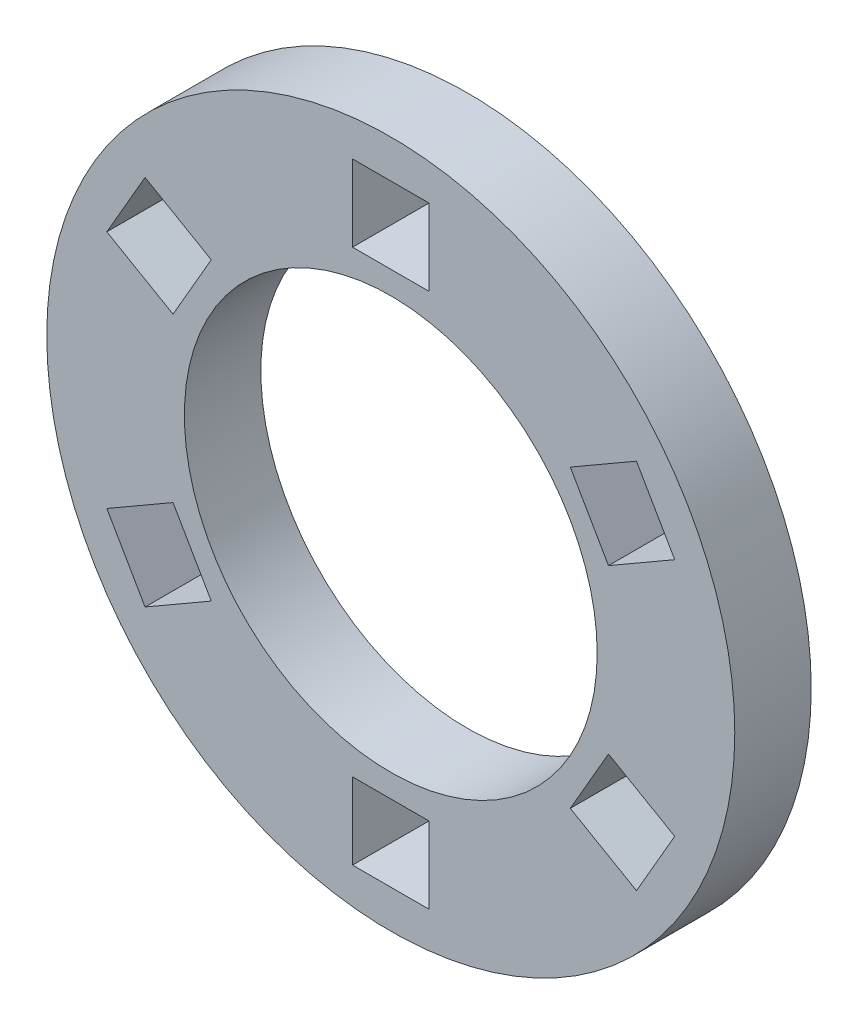
SolidWorks part; units mm, degrees
ref_plane "Front Plane" through (0, 0, 0) normal (0, 0, 1) x (1, 0, 0)
ref_plane "Top Plane" through (0, 0, 0) normal (0, 1, 0) x (1, 0, 0)
ref_plane "Right Plane" through (0, 0, 0) normal (1, 0, 0) x (0, 0, -1)
sketch "Sketch1" plane through (0, 0, 0) normal (0, 0, 1) x (1, 0, 0)
  line L0 (-22.5, 0) -> (22.5, 0) construction
  line L7 (-2.5, 20) -> (2.5, 20)
  line L8 (-2.5, 20) -> (-2.5, 15)
  line L9 (-2.5, 15) -> (2.5, 15)
  line L10 (2.5, 20) -> (2.5, 15)
  line L23 (0, 22.5) -> (0, -22.5) construction
  line L24 (18.5705, 7.8349) -> (14.2404, 5.3349)
  line L25 (11.7404, 9.6651) -> (14.2404, 5.3349)
  line L26 (16.0705, 12.1651) -> (11.7404, 9.6651)
  line L27 (16.0705, 12.1651) -> (18.5705, 7.8349)
  line L28 (16.0705, -12.1651) -> (11.7404, -9.6651)
  line L29 (14.2404, -5.3349) -> (11.7404, -9.6651)
  line L30 (18.5705, -7.8349) -> (14.2404, -5.3349)
  line L31 (18.5705, -7.8349) -> (16.0705, -12.1651)
  line L32 (-2.5, -20) -> (-2.5, -15)
  line L33 (2.5, -15) -> (-2.5, -15)
  line L34 (2.5, -20) -> (2.5, -15)
  line L35 (2.5, -20) -> (-2.5, -20)
  line L36 (-18.5705, -7.8349) -> (-14.2404, -5.3349)
  line L37 (-11.7404, -9.6651) -> (-14.2404, -5.3349)
  line L38 (-16.0705, -12.1651) -> (-11.7404, -9.6651)
  line L39 (-16.0705, -12.1651) -> (-18.5705, -7.8349)
  line L40 (-16.0705, 12.1651) -> (-11.7404, 9.6651)
  line L41 (-14.2404, 5.3349) -> (-11.7404, 9.6651)
  line L42 (-18.5705, 7.8349) -> (-14.2404, 5.3349)
  line L43 (-18.5705, 7.8349) -> (-16.0705, 12.1651)
  circle A0 centre (0, 0) radius 13.5
  circle A1 centre (0, 0) radius 22.5
  point P40 (0, 0)
  dimension "D2" = 45
  dimension "D1" = 27
  dimension "D3" = 5
  dimension "D4" = 5
  dimension "D5" = 15
  dimension "D6" = 6
extrude "Boss-Extrude1" add sketch "Sketch1" along normal blind 5
